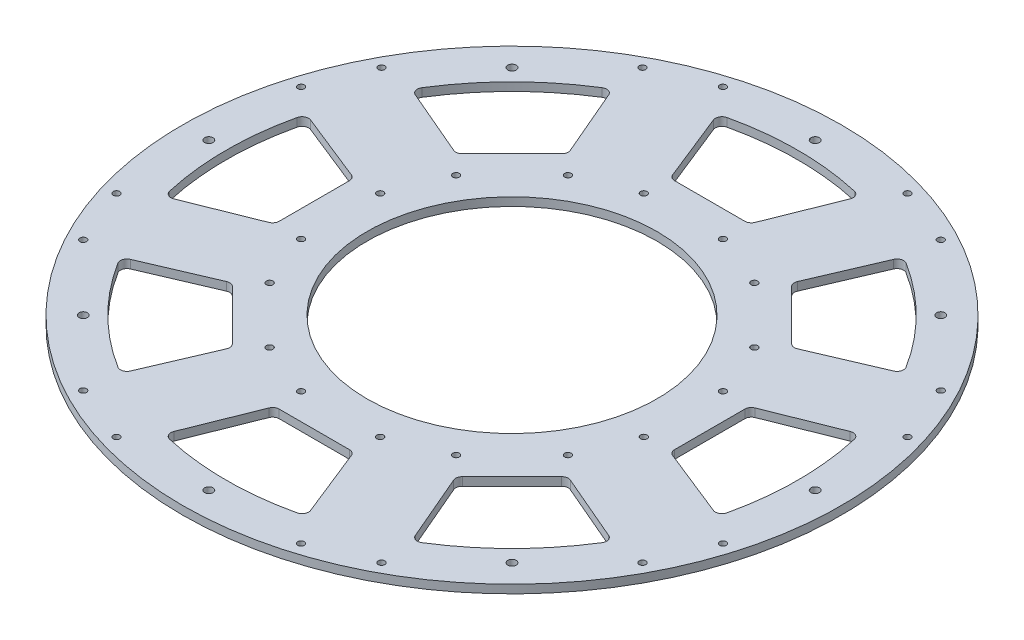
SolidWorks part; units mm, degrees
material "6061 Alloy"
ref_plane "Front Plane" through (0, 0, 0) normal (0, 0, 1) x (1, 0, 0)
ref_plane "Top Plane" through (0, 0, 0) normal (0, 1, 0) x (1, 0, 0)
ref_plane "Right Plane" through (0, 0, 0) normal (1, 0, 0) x (0, 0, -1)
sketch "Sketch1" plane through (0, 0, 0) normal (0, 1, 0) x (1, 0, 0)
  line L0 (-26.6148, 150) -> (26.6148, 150)
  line L1 (-70, 230) -> (70, 230) construction
  line L14 (-70, 230) -> (-30, 130) construction
  line L15 (-30, 130) -> (30, 130) construction
  line L16 (70, 230) -> (30, 130) construction
  line L17 (31.2572, 153.143) -> (51.8583, 204.6457)
  line L18 (-31.2572, 153.143) -> (-51.8583, 204.6457)
  line L19 (86.1863, 130.3907) -> (108.037, 181.3757)
  line L20 (87.2465, 124.8855) -> (124.8855, 87.2465)
  line L21 (130.3907, 86.1863) -> (181.3757, 108.037)
  line L22 (153.143, 31.2572) -> (204.6457, 51.8583)
  line L23 (150, 26.6148) -> (150, -26.6148)
  line L24 (153.143, -31.2572) -> (204.6457, -51.8583)
  line L25 (130.3907, -86.1863) -> (181.3757, -108.037)
  line L26 (124.8855, -87.2465) -> (87.2465, -124.8855)
  line L27 (86.1863, -130.3907) -> (108.037, -181.3757)
  line L28 (31.2572, -153.143) -> (51.8583, -204.6457)
  line L29 (26.6148, -150) -> (-26.6148, -150)
  line L30 (-31.2572, -153.143) -> (-51.8583, -204.6457)
  line L31 (-86.1863, -130.3907) -> (-108.037, -181.3757)
  line L32 (-87.2465, -124.8855) -> (-124.8855, -87.2465)
  line L33 (-130.3907, -86.1863) -> (-181.3757, -108.037)
  line L34 (-153.143, -31.2572) -> (-204.6457, -51.8583)
  line L35 (-150, -26.6148) -> (-150, 26.6148)
  line L36 (-153.143, 31.2572) -> (-204.6457, 51.8583)
  line L37 (-130.3907, 86.1863) -> (-181.3757, 108.037)
  line L38 (-124.8855, 87.2465) -> (-87.2465, 124.8855)
  line L39 (-86.1863, 130.3907) -> (-108.037, 181.3757)
  circle A7 centre (0, 0) radius 250
  circle A10 centre (0, 0) radius 230 construction
  circle A11 centre (0, 230) radius 3 construction
  circle A12 centre (162.6346, 162.6346) radius 3 construction
  circle A13 centre (230, 0) radius 3 construction
  circle A53 centre (-70, 230) radius 3 construction
  circle A54 centre (70, 230) radius 3 construction
  circle A55 centre (30, 130) radius 3 construction
  circle A56 centre (-30, 130) radius 3 construction
  circle A57 centre (212.132, 113.1371) radius 3 construction
  circle A58 centre (113.1371, 70.7107) radius 3 construction
  circle A59 centre (162.6346, -162.6346) radius 3 construction
  circle A60 centre (0, -230) radius 3 construction
  circle A61 centre (-162.6346, -162.6346) radius 3 construction
  circle A62 centre (-230, 0) radius 3 construction
  circle A63 centre (-162.6346, 162.6346) radius 3 construction
  circle A64 centre (0, 0) radius 110
  circle A65 centre (70.7107, 113.1371) radius 3 construction
  circle A66 centre (113.1371, 212.132) radius 3 construction
  circle A67 centre (230, -70) radius 3 construction
  circle A68 centre (130, -30) radius 3 construction
  circle A69 centre (130, 30) radius 3 construction
  circle A70 centre (230, 70) radius 3 construction
  circle A71 centre (113.1371, -212.132) radius 3 construction
  circle A72 centre (70.7107, -113.1371) radius 3 construction
  circle A73 centre (113.1371, -70.7107) radius 3 construction
  circle A74 centre (212.132, -113.1371) radius 3 construction
  circle A75 centre (-70, -230) radius 3 construction
  circle A76 centre (-30, -130) radius 3 construction
  circle A77 centre (30, -130) radius 3 construction
  circle A78 centre (70, -230) radius 3 construction
  circle A79 centre (-212.132, -113.1371) radius 3 construction
  circle A80 centre (-113.1371, -70.7107) radius 3 construction
  circle A81 centre (-70.7107, -113.1371) radius 3 construction
  circle A82 centre (-113.1371, -212.132) radius 3 construction
  circle A83 centre (-230, 70) radius 3 construction
  circle A84 centre (-130, 30) radius 3 construction
  circle A85 centre (-130, -30) radius 3 construction
  circle A86 centre (-230, -70) radius 3 construction
  circle A87 centre (-113.1371, 212.132) radius 3 construction
  circle A88 centre (-70.7107, 113.1371) radius 3 construction
  circle A89 centre (-113.1371, 70.7107) radius 3 construction
  circle A90 centre (-212.132, 113.1371) radius 3 construction
  circle A91 centre (0, 70) radius 3 construction
  circle A92 centre (49.4975, 49.4975) radius 3 construction
  circle A93 centre (70, 0) radius 3 construction
  circle A94 centre (49.4975, -49.4975) radius 3 construction
  circle A95 centre (0, -70) radius 3 construction
  circle A96 centre (-49.4975, -49.4975) radius 3 construction
  circle A97 centre (-70, 0) radius 3 construction
  circle A98 centre (-49.4975, 49.4975) radius 3 construction
  arc A99 (-48.3304, 211.3769) -> (48.3304, 211.3769) centre (0, 0) cw
  arc A100 (51.8583, 204.6457) -> (48.3304, 211.3769) centre (47.2159, 206.5026) ccw
  arc A101 (26.6148, 150) -> (31.2572, 153.143) centre (26.6148, 155) ccw
  arc A102 (-26.6148, 150) -> (-31.2572, 153.143) centre (-26.6148, 155) cw
  arc A103 (-51.8583, 204.6457) -> (-48.3304, 211.3769) centre (-47.2159, 206.5026) cw
  arc A104 (108.037, 181.3757) -> (115.2913, 183.6407) centre (112.6327, 179.4061) cw
  arc A105 (115.2913, 183.6407) -> (183.6407, 115.2913) centre (0, 0) cw
  arc A106 (87.2465, 124.8855) -> (86.1863, 130.3907) centre (90.782, 128.4211) cw
  arc A107 (124.8855, 87.2465) -> (130.3907, 86.1863) centre (128.4211, 90.782) ccw
  arc A108 (181.3757, 108.037) -> (183.6407, 115.2913) centre (179.4061, 112.6327) ccw
  arc A109 (204.6457, 51.8583) -> (211.3769, 48.3304) centre (206.5026, 47.2159) cw
  arc A110 (211.3769, 48.3304) -> (211.3769, -48.3304) centre (0, 0) cw
  arc A111 (150, 26.6148) -> (153.143, 31.2572) centre (155, 26.6148) cw
  arc A112 (150, -26.6148) -> (153.143, -31.2572) centre (155, -26.6148) ccw
  arc A113 (204.6457, -51.8583) -> (211.3769, -48.3304) centre (206.5026, -47.2159) ccw
  arc A114 (181.3757, -108.037) -> (183.6407, -115.2913) centre (179.4061, -112.6327) cw
  arc A115 (183.6407, -115.2913) -> (115.2913, -183.6407) centre (0, 0) cw
  arc A116 (124.8855, -87.2465) -> (130.3907, -86.1863) centre (128.4211, -90.782) cw
  arc A117 (87.2465, -124.8855) -> (86.1863, -130.3907) centre (90.782, -128.4211) ccw
  arc A118 (108.037, -181.3757) -> (115.2913, -183.6407) centre (112.6327, -179.4061) ccw
  arc A119 (51.8583, -204.6457) -> (48.3304, -211.3769) centre (47.2159, -206.5026) cw
  arc A120 (48.3304, -211.3769) -> (-48.3304, -211.3769) centre (0, 0) cw
  arc A121 (26.6148, -150) -> (31.2572, -153.143) centre (26.6148, -155) cw
  arc A122 (-26.6148, -150) -> (-31.2572, -153.143) centre (-26.6148, -155) ccw
  arc A123 (-51.8583, -204.6457) -> (-48.3304, -211.3769) centre (-47.2159, -206.5026) ccw
  arc A124 (-108.037, -181.3757) -> (-115.2913, -183.6407) centre (-112.6327, -179.4061) cw
  arc A125 (-115.2913, -183.6407) -> (-183.6407, -115.2913) centre (0, 0) cw
  arc A126 (-87.2465, -124.8855) -> (-86.1863, -130.3907) centre (-90.782, -128.4211) cw
  arc A127 (-124.8855, -87.2465) -> (-130.3907, -86.1863) centre (-128.4211, -90.782) ccw
  arc A128 (-181.3757, -108.037) -> (-183.6407, -115.2913) centre (-179.4061, -112.6327) ccw
  arc A129 (-204.6457, -51.8583) -> (-211.3769, -48.3304) centre (-206.5026, -47.2159) cw
  arc A130 (-211.3769, -48.3304) -> (-211.3769, 48.3304) centre (0, 0) cw
  arc A131 (-150, -26.6148) -> (-153.143, -31.2572) centre (-155, -26.6148) cw
  arc A132 (-150, 26.6148) -> (-153.143, 31.2572) centre (-155, 26.6148) ccw
  arc A133 (-204.6457, 51.8583) -> (-211.3769, 48.3304) centre (-206.5026, 47.2159) ccw
  arc A134 (-181.3757, 108.037) -> (-183.6407, 115.2913) centre (-179.4061, 112.6327) cw
  arc A135 (-183.6407, 115.2913) -> (-115.2913, 183.6407) centre (0, 0) cw
  arc A136 (-124.8855, 87.2465) -> (-130.3907, 86.1863) centre (-128.4211, 90.782) cw
  arc A137 (-87.2465, 124.8855) -> (-86.1863, 130.3907) centre (-90.782, 128.4211) ccw
  arc A138 (-108.037, 181.3757) -> (-115.2913, 183.6407) centre (-112.6327, 179.4061) ccw
  point P28 (0, 0)
  point P32 (0, 230)
  point P38 (0, 130)
  point P95 (0, 0)
  point P113 (0, 0)
  point P118 (0, 150)
  point P119 (0, 216.8317)
  point P123 (54, 210)
  point P126 (30, 150)
  point P129 (-30, 150)
  point P132 (-54, 210)
  point P217 (0, 0)
  dimension "D1" = 460
  dimension "D2" = 8
  dimension "D4" = 500
  dimension "D5" = 220
  dimension "D7" = 60
  dimension "D8" = 6
  dimension "D10" = 140
  dimension "D12" = 60
  dimension "D3" = 6
  dimension "D17" = 5
  dimension "D9" = 130
  dimension "D6" = 100
  dimension "D14" = 60
  dimension "D15" = 20
  dimension "D16" = 60
  dimension "D11" = 8
  dimension "D13" = 8
  dimension "D18" = 8
extrude "Boss-Extrude1" add sketch "Sketch1" against normal blind 6.35 contours A7
hole_wizard "M6 Clearance Hole1" positions "3DSketch1" profile "Sketch2" hole size "M6" standard "ANSI Metric" end condition through all
sketch3d "3DSketch1"
  point P0 (0, 0, -230)
  point P2 (-162.6346, 0, -162.6346)
  point P4 (-230, 0, 0)
  point P6 (162.6346, 0, -162.6346)
  point P8 (230, 0, 0)
  point P10 (162.6346, 0, 162.6346)
  point P12 (0, 0, 230)
  point P14 (-162.6346, 0, 162.6346)
sketch "Sketch2" plane through (0, 0, -230) normal (1, 0, 0) x (0, 0, 1)
  line L0 (0, 0) -> (0, 6.35)
  line L1 (0, 6.35) -> (3.2, 6.35)
  line L2 (3.2, 6.35) -> (3.2, 0)
  line L5 (3.2, 0) -> (0, 0)
  line L11 (0, -6.35) -> (0, 107.95) construction
  dimension "Thru Hole Dia." = 6.4
  dimension "Thru Hole Depth" = 6.35
hole_wizard "Tap Drill for M6x1.0 Tap2" positions "3DSketch2" profile "Sketch3" hole size "M6x1.0" standard "ANSI Metric" end condition through all
sketch3d "3DSketch2"
  point P0 (-70, 0, -230)
  point P2 (70, 0, -230)
  point P4 (30, 0, -130)
  point P6 (-30, 0, -130)
sketch "Sketch3" plane through (-70, 0, -230) normal (1, 0, 0) x (0, 0, 1)
  line L0 (0, 0) -> (0, 6.35)
  line L1 (0, 6.35) -> (2.5, 6.35)
  line L2 (2.5, 6.35) -> (2.5, 0)
  line L5 (2.5, 0) -> (0, 0)
  line L11 (0, -6.35) -> (0, 107.95) construction
  dimension "Thru Hole Dia." = 5
  dimension "Thru Hole Depth" = 6.35
pattern_circular "CirPattern1" count 8 over 360 about axis through (0, 0, 0) along (0, 1, 0) of "Tap Drill for M6x1.0 Tap2"
